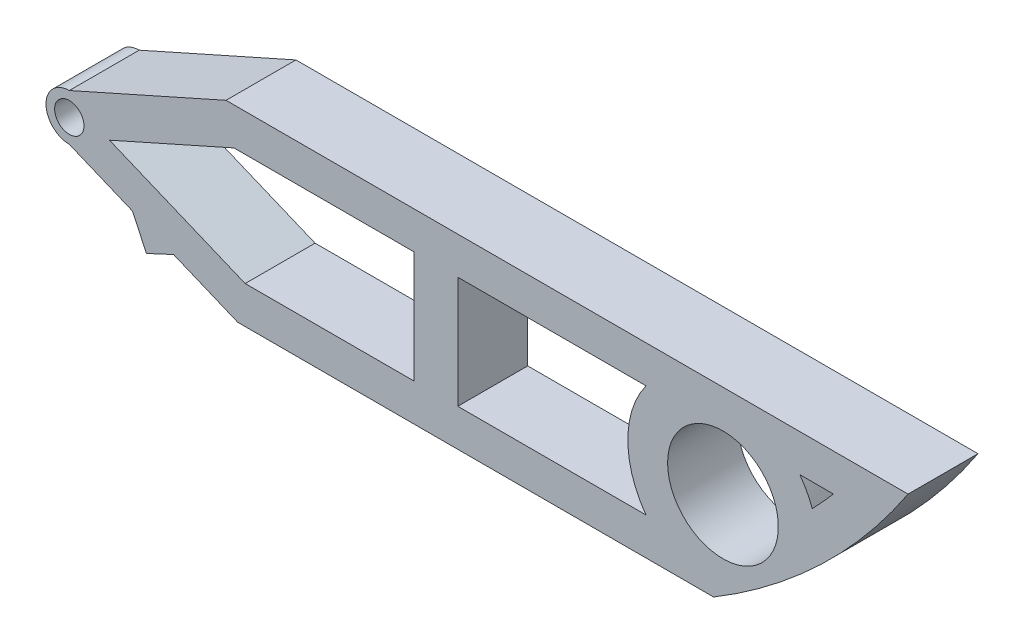
SolidWorks part; units mm, degrees
ref_plane "Front Plane" through (0, 0, 0) normal (0, 0, 1) x (1, 0, 0)
ref_plane "Top Plane" through (0, 0, 0) normal (0, 1, 0) x (1, 0, 0)
ref_plane "Right Plane" through (0, 0, 0) normal (1, 0, 0) x (0, 0, -1)
sketch "Sketch1" plane through (0, 0, 0) normal (0, 0, 1) x (1, 0, 0)
  line L1 (120.65, 25.4) -> (-120.65, 25.4)
  line L2 (120.65, 25.4) -> (120.65, -25.4)
  line L3 (120.65, -25.4) -> (-120.65, -25.4)
  line L4 (-120.65, 25.4) -> (-120.65, -25.4)
  line L5 (120.65, 25.4) -> (-120.65, -25.4) construction
  line L6 (120.65, -25.4) -> (-120.65, 25.4) construction
  point P0 (0, 0)
  dimension "D1" = 241.3
  dimension "D2" = 50.8
extrude "Boss-Extrude1" add sketch "Sketch1" along normal blind 19.06
sketch "Sketch3" plane through (0, 0, 19.06) normal (0, 0, 1) x (1, 0, 0)
  line L0 (0, 0) -> (-120.65, 0) construction
  line L1 (-120.65, 25.4) -> (-120.65, -25.4) construction
  circle A0 centre (-107.95, 0) radius 4
  dimension "D2" = 8
  dimension "D1" = 12.7
extrude "Cut-Extrude1" cut sketch "Sketch3" against normal through all
sketch "Sketch5" plane through (0, 0, 19.06) normal (0, 0, 1) x (1, 0, 0)
  line L0 (-120.65, -25.4) -> (120.65, -25.4) construction
  line L1 (-107.95, -6.35) -> (-62.0461, -25.4)
  line L2 (-107.95, 6.35) -> (-65.2393, 25.4)
  line L3 (120.65, 25.4) -> (-120.65, 25.4) construction
  line L4 (-65.2393, 25.4) -> (-120.65, 25.4)
  line L5 (-120.65, 25.4) -> (-120.65, -25.4)
  line L6 (-120.65, -25.4) -> (-62.0461, -25.4)
  line L7 (120.65, 25.4) -> (120.65, -25.4)
  line L8 (120.65, -25.4) -> (67.6371, -25.4)
  arc A0 (67.6371, -25.4) -> (120.65, 25.4) centre (-17.2255, 116.2204) ccw
  arc A2 (-107.95, 6.35) -> (-107.95, -6.35) centre (-107.95, 0) ccw
  line M3 (-120.65, 25.4) -> (-120.65, -25.4)
  line M4 (-120.65, -25.4) -> (120.65, -25.4)
  line M5 (120.65, -25.4) -> (120.65, 25.4)
  line M6 (120.65, 25.4) -> (-120.65, 25.4)
  dimension "D1" = 165.1
  dimension "D2" = 12.7
extrude "Cut-Extrude2" cut sketch "Sketch5" against normal through all contours A0 L8 M5 | A2 L2 L1 M6 M3 M4
sketch "Sketch6" plane through (0, 0, 19.06) normal (0, 0, 1) x (1, 0, 0)
  line L0 (-107.95, 0) -> (100.0384, 0) construction
  arc A0 (67.6371, -25.4) -> (120.65, 25.4) centre (-17.2255, 116.2204) ccw construction
  circle A1 centre (19.05, 0) radius 3.1347
  dimension "D1" = 127
sketch "Sketch7" plane through (0, 0, 0) normal (0, 0, -1) x (-1, 0, 0)
  line L0 (44.0204, -2.9977) -> (44.0204, 16.0523) construction
  point P3 (44.0204, -2.9977)
  point P4 (44.0204, 16.0523)
  dimension "D1" = 19.05
sketch "Sketch11" plane through (0, 0, 0) normal (0, 0, -1) x (-1, 0, 0)
  line L1 (107.95, 0) -> (-100.0384, 0) construction
  circle A1 centre (-70.2, 0) radius 15.09
  circle A2 centre (107.95, 0) radius 4 construction
  dimension "D1" = 30.18
  dimension "D2" = 178.15
extrude "Cut-Extrude3" cut sketch "Sketch11" against normal through all
sketch "Sketch12" plane through (0, 0, 0) normal (0, 0, -1) x (-1, 0, 0)
  line L3 (86.9395, -21.6025) -> (79.5264, -18.1457)
  line L4 (107.95, -6.35) -> (62.0461, -25.4) construction
  line L5 (79.5264, -18.1457) -> (90.717, -13.5016)
  line L6 (90.717, -13.5016) -> (86.9395, -21.6025)
  point P8 (88.9769, -14.2238)
  dimension "D1" = 90
  dimension "D2" = 8.1795
  dimension "D3" = 137.538
extrude "Boss-Extrude2" add sketch "Sketch12" against normal up to surface (19.06 mm away) up to face at (55.11, 0, 19.06)
sketch "Sketch13" plane through (0, 0, 0) normal (0, 0, -1) x (-1, 0, 0)
  line L0 (-91.178, 15.24) -> (-100.2877, 15.24)
  line L1 (13.9845, -15.24) -> (60.0216, -15.24)
  line L3 (2.0742, -15.24) -> (2.0742, 15.24)
  line L5 (13.9845, -15.24) -> (13.9845, 15.24)
  line L6 (2.0742, 15.24) -> (-49.222, 15.24)
  line L7 (79.7648, -7.0466) -> (83.1771, -5.6305)
  line L14 (63.0762, 15.24) -> (-100.2877, 15.24)
  line L15 (-64.7779, -15.24) -> (60.0216, -15.24)
  line L16 (60.0216, -15.24) -> (79.7648, -7.0466)
  line L17 (79.7648, -7.0466) -> (82.0252, -8.1007)
  line L18 (82.0252, -8.1007) -> (83.1771, -5.6305)
  line L19 (83.1771, -5.6305) -> (97.0038, 0.1075)
  line L20 (97.0038, 0.1075) -> (63.0762, 15.24)
  line L21 (63.0762, 15.24) -> (13.9845, 15.24)
  line L22 (-49.222, -15.24) -> (2.0742, -15.24)
  line L23 (60.0216, -15.24) -> (79.7648, -7.0466)
  line L26 (83.1771, -5.6305) -> (97.0038, 0.1075)
  line L27 (97.0038, 0.1075) -> (63.0762, 15.24)
  arc A0 (-91.178, 15.24) -> (-94.5467, 8.9201) centre (-70.2, 0) ccw
  arc A2 (-49.222, -15.24) -> (-49.222, 15.24) centre (-70.2, 0) ccw
  arc A4 (-100.2877, 15.24) -> (-64.7779, -15.24) centre (17.2255, 116.2204) ccw
  arc A5 (-100.2877, 15.24) -> (-94.5467, 8.9201) centre (17.2255, 116.2204) ccw
  dimension "D1" = 10.16
extrude "Cut-Extrude4" cut sketch "Sketch13" against normal through all
